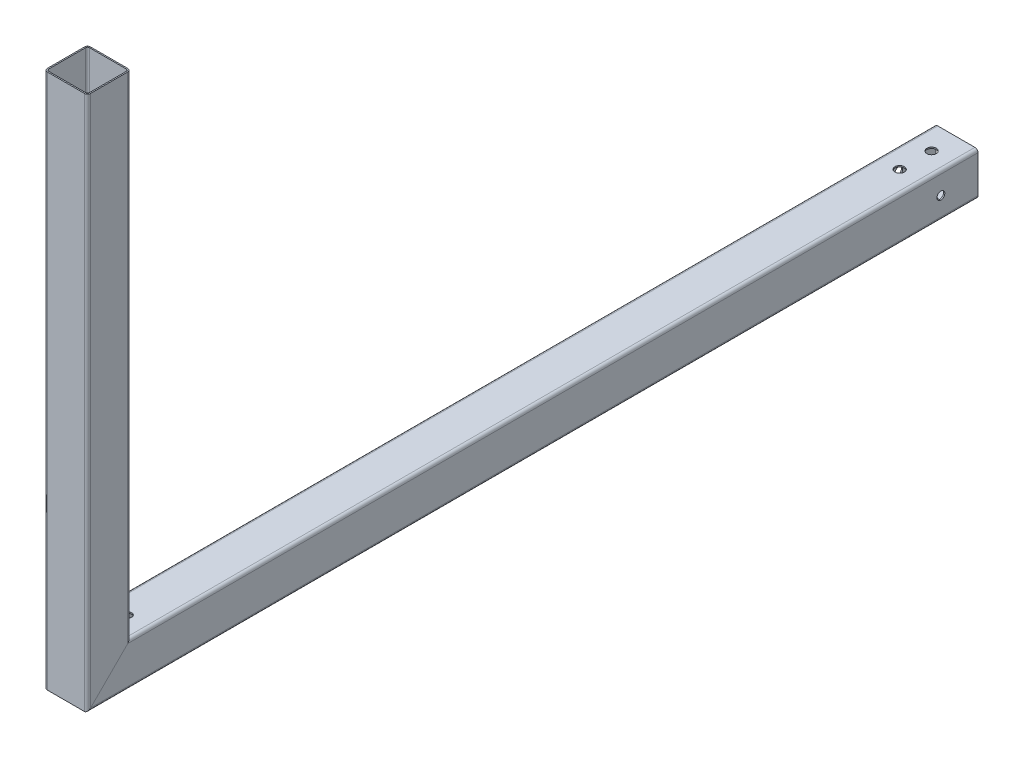
SolidWorks part; units mm, degrees
ref_plane "Alzado" through (0, 0, 0) normal (0, 0, 1) x (1, 0, 0)
ref_plane "Planta" through (0, 0, 0) normal (0, 1, 0) x (1, 0, 0)
ref_plane "Vista lateral" through (0, 0, 0) normal (1, 0, 0) x (0, 0, -1)
sketch "Croquis1" plane through (0, 0, 0) normal (1, 0, 0) x (0, 0, -1)
  line L0 (-701.985, 415) -> (-701.985, -415)
  line L1 (701.985, -415) -> (-701.985, -415) construction
  line L2 (701.985, -415) -> (701.985, 415) construction
  line L3 (701.985, 415) -> (-701.985, 415) construction
  line L4 (-701.985, -415) -> (-701.985, 415) construction
  line L5 (701.985, -415) -> (-701.985, 415) construction
  line L6 (701.985, 415) -> (-701.985, -415) construction
  line L7 (-701.985, -415) -> (701.985, -415)
  point P0 (0, 0)
  dimension "D1" = 1403.97
  dimension "D2" = 830
other "Tubo cuadrado 3 X 3 X 0.25(1)"
ref_plane "Plano1" through (0, -415, 701.985) normal (0, 0, -1) x (0, 1, 0)
sketch "Sketch1" plane through (0, -415, 701.985) normal (0, 0, -1) x (0, 1, 0)
  line L0 (-30, -33) -> (30, -33)
  line L1 (-33, -30) -> (-33, 30)
  line L2 (30, 33) -> (-30, 33)
  line L3 (33, 30) -> (33, -30)
  line L4 (-30, -35) -> (30, -35)
  line L5 (-35, -30) -> (-35, 30)
  line L6 (30, 35) -> (-30, 35)
  line L7 (35, 30) -> (35, -30)
  line L8 (0, 0) -> (33, 0) construction
  line L9 (0, 0) -> (0, 33) construction
  arc A0 (35, 30) -> (30, 35) centre (30, 30) ccw
  arc A1 (30, -35) -> (35, -30) centre (30, -30) ccw
  arc A2 (-35, -30) -> (-30, -35) centre (-30, -30) ccw
  arc A3 (-30, 35) -> (-35, 30) centre (-30, 30) ccw
  arc A4 (-30, 33) -> (-33, 30) centre (-30, 30) ccw
  arc A5 (33, 30) -> (30, 33) centre (30, 30) ccw
  arc A6 (30, -33) -> (33, -30) centre (30, -30) ccw
  arc A7 (-33, -30) -> (-30, -33) centre (-30, -30) ccw
  point P3 (0, 35)
  point P4 (35, 0)
  point P5 (0, -35)
  point P6 (-35, 0)
  point P7 (-35, 35)
  point P8 (-35, -35)
  point P33 (0, 0)
  point P35 (35, -35)
  point P36 (35, 35)
  point P37 (0, 0)
  dimension "D1" = 5
  dimension "Thickness" = 2
  dimension "V_leg" = 70
sketch "Croquis3" plane through (0, -380, 0) normal (0, 1, 0) x (1, 0, 0)
  line L0 (30, 701.985) -> (-30, 701.985) construction
  line L1 (-30, -666.985) -> (30, -666.985) construction
  circle A0 centre (0, 661.985) radius 7.6109
  circle A1 centre (0, 610.3832) radius 7.6109
  circle A2 centre (0, -636.985) radius 6.35
  dimension "D1" = 91.6018
  dimension "D3" = 12.7
  dimension "D2" = 40
  dimension "D4" = 30
extrude "Cortar-Extruir1" cut sketch "Croquis3" against normal through all
sketch "Croquis4" plane through (35, 0, 0) normal (1, 0, 0) x (0, 0, -1)
  line L0 (-658.015, -415) -> (701.985, -415) construction
  line L2 (701.985, -385) -> (701.985, -445) construction
  circle A0 centre (641.985, -415) radius 6.35
  dimension "D1" = 12.7
  dimension "D2" = 60
extrude "Cortar-Extruir2" cut sketch "Croquis4" against normal through all
